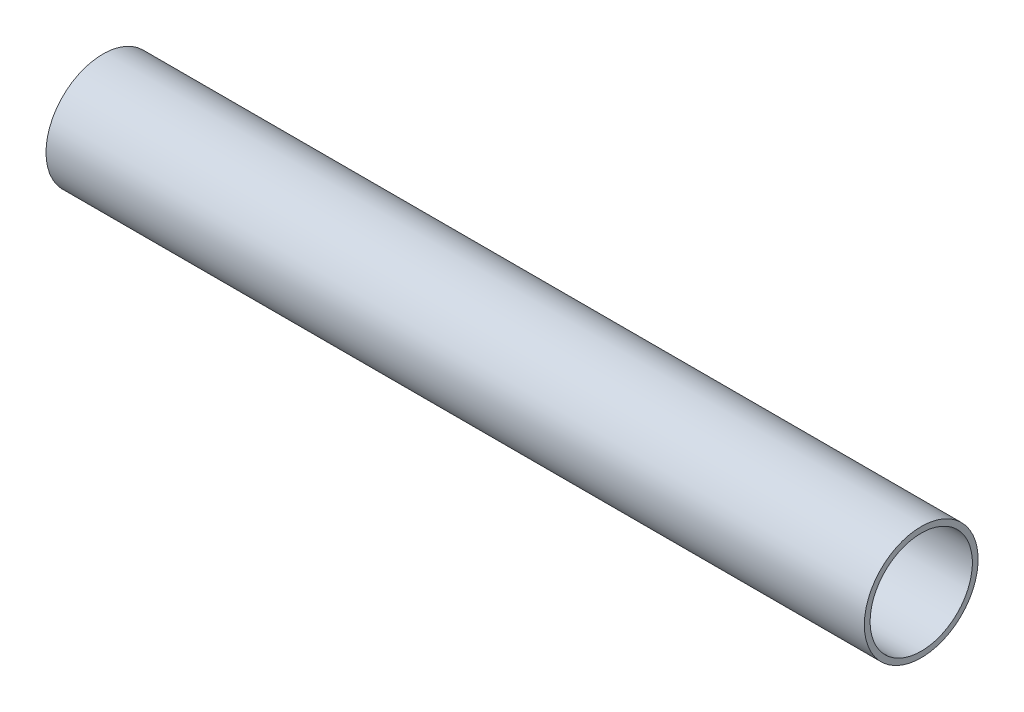
SolidWorks part; units mm, degrees
ref_plane "Front Plane" through (0, 0, 0) normal (0, 0, 1) x (1, 0, 0)
ref_plane "Top Plane" through (0, 0, 0) normal (0, 1, 0) x (1, 0, 0)
ref_plane "Right Plane" through (0, 0, 0) normal (1, 0, 0) x (0, 0, -1)
sketch "Sketch1" plane through (0, 0, 0) normal (0, 0, 1) x (1, 0, 0)
  line L0 (-93.5748, 0) -> (130.7243, 0) construction
  line L1 (0, 12.5) -> (98.8626, 12.5)
  line L2 (98.8626, 12.5) -> (98.8626, 6.25)
  line L3 (98.8626, 6.25) -> (100.8626, 7.5639)
  line L4 (100.8626, 7.5639) -> (100.8626, 12.5)
  line L5 (0, 13.904) -> (200, 13.904)
  line L6 (0, 12.5) -> (0, 13.904)
  line L7 (200, 12.5) -> (200, 13.904)
  line L8 (100.8626, 12.5) -> (200, 12.5)
  dimension "D1" = 12.5
  dimension "D2" = 200
  dimension "D3" = 2
  dimension "D4" = 6.25
revolve "Revolve1" add sketch "Sketch1" angle 360 about L0
